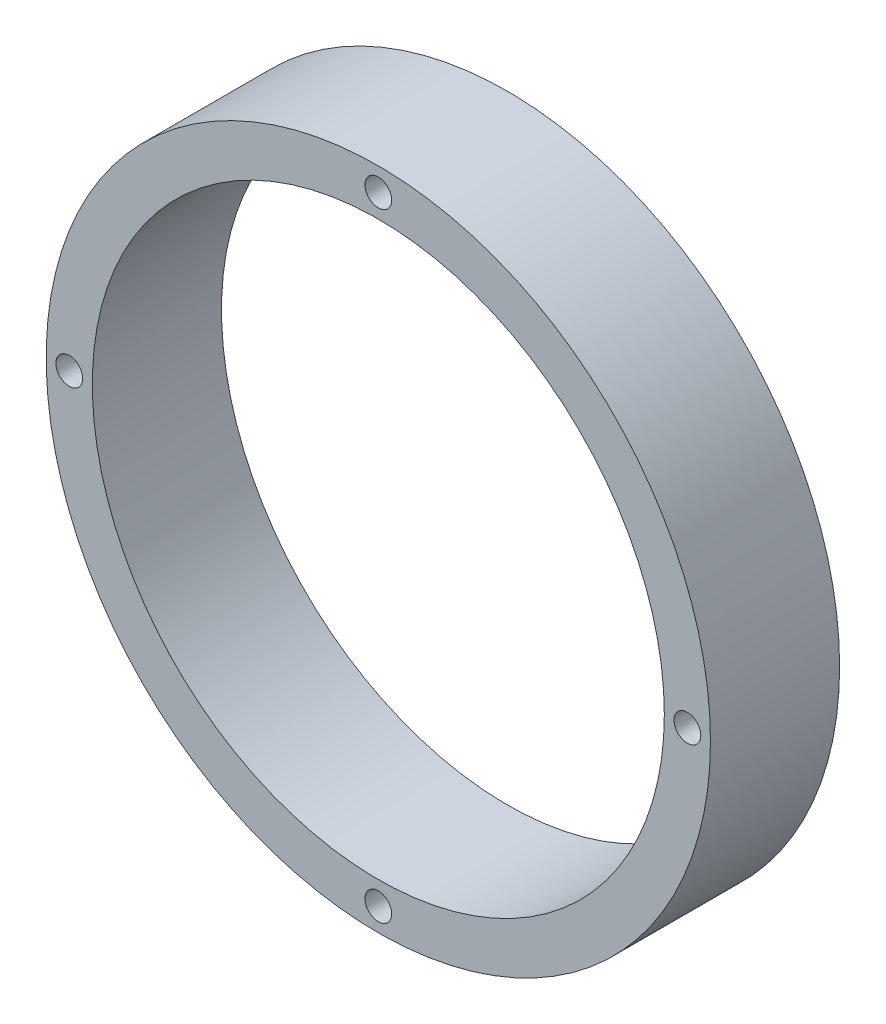
SolidWorks part; units mm, degrees
ref_plane "Front Plane" through (0, 0, 0) normal (0, 0, 1) x (1, 0, 0)
ref_plane "Top Plane" through (0, 0, 0) normal (0, 1, 0) x (1, 0, 0)
ref_plane "Right Plane" through (0, 0, 0) normal (1, 0, 0) x (0, 0, -1)
sketch "Sketch1" plane through (0, 0, 0) normal (0, 0, 1) x (1, 0, 0)
  circle A0 centre (0, 0) radius 36
  circle A1 centre (0, 0) radius 31
  dimension "D1" = 62
  dimension "D2" = 5
extrude "Boss-Extrude1" add sketch "Sketch1" along normal blind 14
sketch "Sketch2" plane through (0, 0, 14) normal (0, 0, 1) x (1, 0, 0)
  circle A0 centre (0, 33.5) radius 1.45
  circle A3 centre (0, 0) radius 36 construction
  dimension "D1" = 2.9
  dimension "D2" = 33.5
extrude "Cut-Extrude1" cut sketch "Sketch2" against normal through all
pattern_circular "CirPattern1" count 4 over 360 about axis through (0, 0, 0) along (0, 0, 1) of "Cut-Extrude1"
